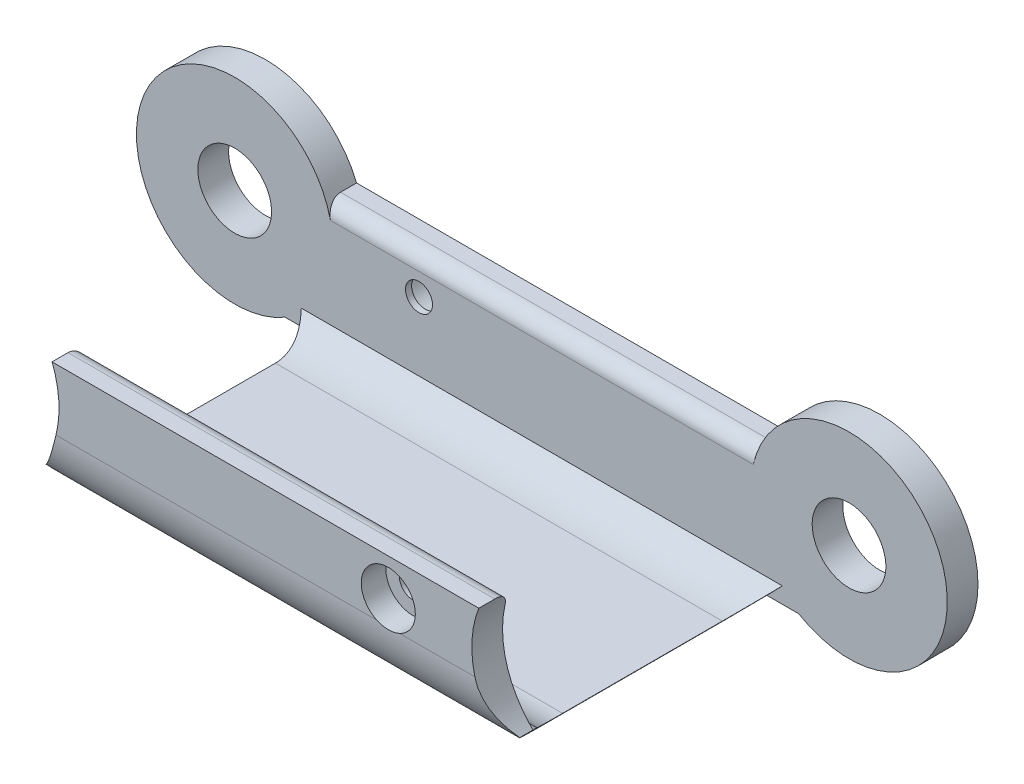
SolidWorks part; units mm, degrees
ref_plane "前视基准面" through (0, 0, 0) normal (0, 0, 1) x (1, 0, 0)
ref_plane "上视基准面" through (0, 0, 0) normal (0, 1, 0) x (1, 0, 0)
ref_plane "右视基准面" through (0, 0, 0) normal (1, 0, 0) x (0, 0, -1)
sketch "草图1" plane through (0, 0, 0) normal (0, 1, 0) x (1, 0, 0)
  line L1 (25, -12.5) -> (-25, -12.5)
  line L2 (25, -12.5) -> (25, 12.5)
  line L3 (25, 12.5) -> (-25, 12.5)
  line L4 (-25, -12.5) -> (-25, 12.5)
  line L5 (25, -12.5) -> (-25, 12.5) construction
  line L6 (25, 12.5) -> (-25, -12.5) construction
  point P0 (0, 0)
extrude "凸台-拉伸1" add sketch "草图1" along normal blind 11
sketch "草图2" plane through (25, 0, 0) normal (1, 0, 0) x (0, 0, -1)
  line L0 (-12.5, 0) -> (12.5, 0) construction
  line L1 (0, 0) -> (0, 6.1663) construction
  line L2 (-12.5, 0) -> (-6.5, 0)
  line L3 (-12.5, 6) -> (-12.5, 0)
  line L5 (12.5, 6) -> (12.5, 0)
  line L6 (12.5, 0) -> (6.5, 0)
  arc A0 (6.5, 0) -> (12.5, 6) centre (6.5, 6) ccw
  arc A1 (-6.5, 0) -> (-12.5, 6) centre (-6.5, 6) cw
  point P9 (12.5, 0)
  dimension "D1" = 6
extrude "切除-拉伸1" cut sketch "草图2" against normal through all
sketch "草图3" plane through (25, 0, 0) normal (1, 0, 0) x (0, 0, -1)
  line L0 (-10, 11) -> (10, 11)
  line L1 (-12.5, 11) -> (12.5, 11) construction
  line L2 (10, 11) -> (10, 2.4293)
  line L3 (0, 11) -> (0, 4.0635) construction
  line L4 (6.5, 1) -> (-6.5, 1)
  line L5 (-10, 11) -> (-10, 2.4293)
  arc A0 (10, 2.4293) -> (6.5, 1) centre (6.5, 6) cw
  arc A1 (-10, 2.4293) -> (-6.5, 1) centre (-6.5, 6) ccw
  point P9 (0, 0)
  point P15 (0, 1)
extrude "切除-拉伸2" cut sketch "草图3" against normal through all
sketch "草图6" plane through (0, 0, -12.5) normal (0, 0, -1) x (-1, 0, 0)
  line L0 (25, 11) -> (25, 6) construction
  line L1 (-25, 11) -> (-25, 6) construction
  circle A1 centre (25, 8) radius 8
  circle A2 centre (-25, 8) radius 8
extrude "凸台-拉伸4" add sketch "草图6" against normal blind 2.5
sketch "草图9" plane through (0, 0, 12.5) normal (0, 0, 1) x (1, 0, 0)
  circle A0 centre (25, 8) radius 3
  circle A1 centre (10, 8) radius 1.1
extrude "切除-拉伸4" cut sketch "草图9" against normal blind 2.5
sketch "草图11" plane through (0, 0, -12.5) normal (0, 0, -1) x (-1, 0, 0)
  circle A0 centre (10, 8) radius 2.2
sketch "草图12" plane through (0, 0, 12.5) normal (0, 0, 1) x (1, 0, 0)
  circle A0 centre (10, 8) radius 2.2
extrude "切除-拉伸5" cut sketch "草图12" against normal blind 2
extrude "切除-拉伸6" cut sketch "草图11" against normal blind 2
sketch "草图13" plane through (0, 0, 12.5) normal (0, 0, 1) x (1, 0, 0)
  line L0 (-25, 11) -> (-25, 6) construction
  circle A0 centre (-25, 8) radius 8.2
  circle A1 centre (25, 8) radius 8.2
extrude "切除-拉伸7" cut sketch "草图13" against normal blind 2.5
sketch "草图14" plane through (0, 0, -12.5) normal (0, 0, -1) x (-1, 0, 0)
  circle A0 centre (25, 8) radius 3
  circle A1 centre (-25, 8) radius 3
  circle A2 centre (10, 8) radius 1.1
extrude "切除-拉伸8" cut sketch "草图14" against normal blind 2.5
sketch "草图15" plane through (0, 0, -10) normal (0, 0, 1) x (1, 0, 0)
  line L0 (25, 8) -> (25, 0)
  line L1 (25, 0) -> (17.0029, -0.2165)
  line L2 (17.0029, -0.2165) -> (25, 8)
  line L3 (0, 0) -> (0, 19.4595) construction
  line L4 (-17.0029, -0.2165) -> (-25, 8)
  line L5 (-25, 8) -> (-25, 0)
  line L6 (-25, 0) -> (-17.0029, -0.2165)
extrude "切除-拉伸9" cut sketch "草图15" along normal blind 25
fillet "圆角1" radius 1.2 2 edges at (0, 11, -10) (0, 11, 10)
